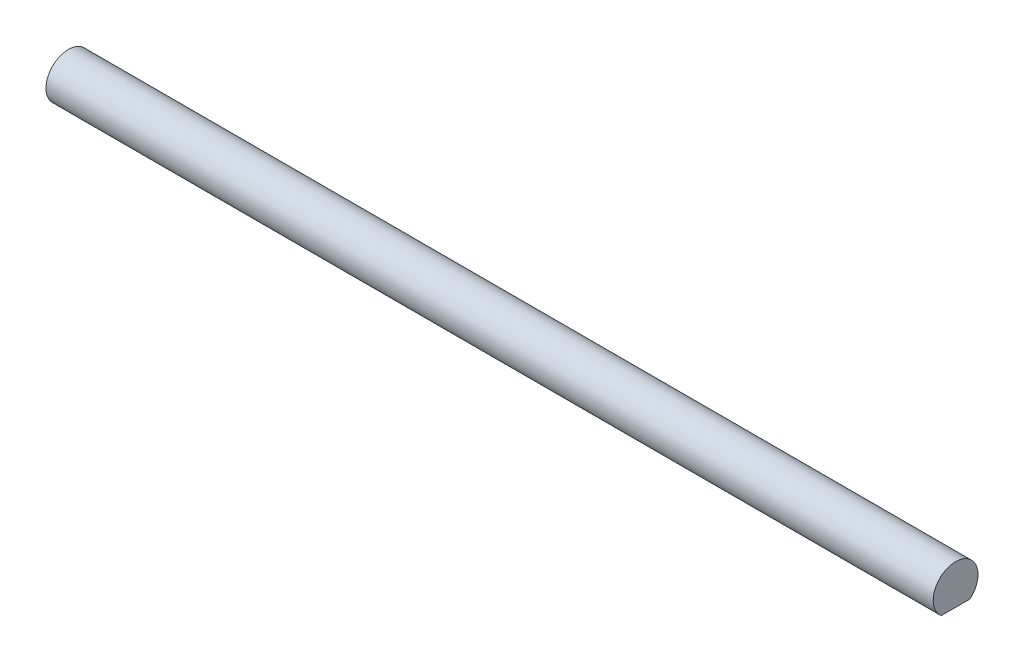
SolidWorks part; units mm, degrees
ref_plane "Front Plane" through (0, 0, 0) normal (0, 0, 1) x (1, 0, 0)
ref_plane "Top Plane" through (0, 0, 0) normal (0, 1, 0) x (1, 0, 0)
ref_plane "Right Plane" through (0, 0, 0) normal (1, 0, 0) x (0, 0, -1)
sketch "Sketch1" plane through (0, 0, 0) normal (1, 0, 0) x (0, 0, -1)
  line L0 (-2.032, -2.4396) -> (2.032, -2.4396)
  circle A0 centre (0, 0) radius 3.175
  dimension "D1" = 6.35
  dimension "D2" = 4.064
extrude "Boss-Extrude1" add sketch "Sketch1" along normal blind 304.8 contours L0 A0
sketch "Sketch2" [suppressed] plane through (304.8, 0, 0) normal (1, 0, 0) x (0, 0, -1)
  circle A0 centre (0, 0) radius 3.175
extrude "Cut-Extrude1" [suppressed] cut sketch "Sketch2" against normal blind 190.5
sketch "Sketch3" [suppressed] plane through (304.8, 0, 0) normal (1, 0, 0) x (0, 0, -1)
  circle A0 centre (0, 0) radius 3.175
extrude "Cut-Extrude2" [suppressed] cut sketch "Sketch3" against normal blind 228.6
sketch "Sketch4" plane through (304.8, 0, 0) normal (1, 0, 0) x (0, 0, -1)
  circle A0 centre (0, 0) radius 3.175
  dimension "D1" = 6.35
extrude "Cut-Extrude3" cut sketch "Sketch4" against normal blind 179.07
